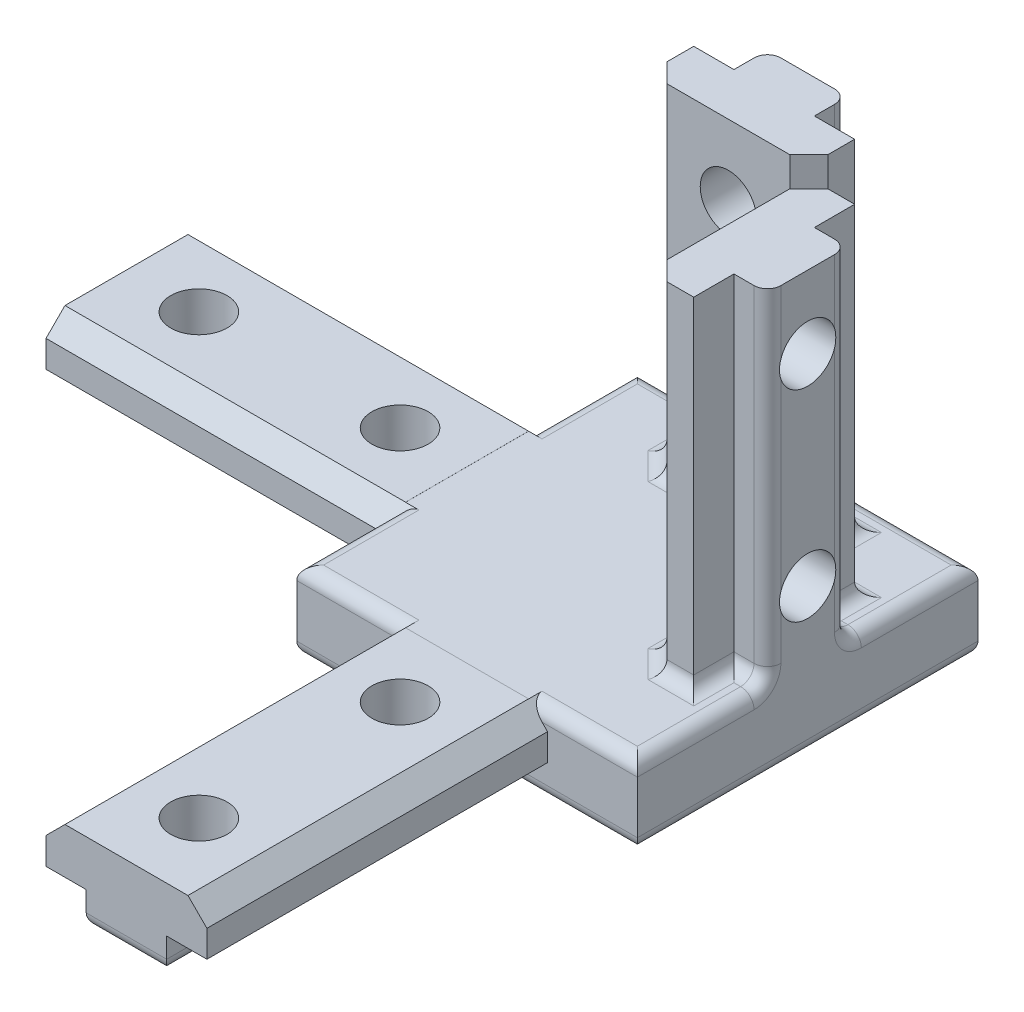
SolidWorks part; units mm, degrees
ref_plane "Front Plane" through (0, 0, 0) normal (0, 0, 1) x (1, 0, 0)
ref_plane "Top Plane" through (0, 0, 0) normal (0, 1, 0) x (1, 0, 0)
ref_plane "Right Plane" through (0, 0, 0) normal (1, 0, 0) x (0, 0, -1)
sketch "Sketch1" plane through (0, 0, 0) normal (0, 1, 0) x (1, 0, 0)
  line L1 (-12.7, 12.7) -> (12.7, 12.7)
  line L2 (-12.7, 12.7) -> (-12.7, -12.7)
  line L3 (-12.7, -12.7) -> (12.7, -12.7)
  line L4 (12.7, 12.7) -> (12.7, -12.7)
  line L5 (-12.7, 12.7) -> (12.7, -12.7) construction
  line L6 (-12.7, -12.7) -> (12.7, 12.7) construction
  point P0 (0, 0)
  dimension "D1" = 25.4
extrude "Boss-Extrude1" add sketch "Sketch1" along normal blind 5.91
sketch "Sketch2" plane through (0, 0, 12.7) normal (0, 0, 1) x (1, 0, 0)
  line L0 (-3, 0) -> (3, 0)
  line L1 (-12.7, 0) -> (12.7, 0) construction
  line L2 (3, 0) -> (3, 2.5)
  line L3 (3, 2.5) -> (6, 2.5)
  line L4 (6, 2.5) -> (6, 4.5)
  line L5 (6, 4.5) -> (4.5858, 5.9142)
  line L6 (4.5858, 5.9142) -> (-4.5858, 5.9142)
  line L7 (0, 0) -> (0, 6.6193) construction
  line L8 (-6, 4.5) -> (-4.5858, 5.9142)
  line L9 (-6, 2.5) -> (-6, 4.5)
  line L10 (-3, 2.5) -> (-6, 2.5)
  line L11 (-3, 0) -> (-3, 2.5)
  point P14 (0, 5.9142)
  point P18 (0, 0)
  dimension "D1" = 6
  dimension "D2" = 12
  dimension "D3" = 135
  dimension "D4" = 2.5
  dimension "D5" = 2
extrude "Boss-Extrude2" add sketch "Sketch2" along normal blind 25.4
sketch "Sketch3" plane through (-12.7, 0, 0) normal (-1, 0, 0) x (0, 0, 1)
  line L0 (-3, 0) -> (3, 0)
  line L1 (3, 0) -> (3, 2.5)
  line L2 (3, 2.5) -> (6, 2.5)
  line L3 (6, 2.5) -> (6, 4.5)
  line L4 (6, 4.5) -> (4.5858, 5.9142)
  line L5 (4.5858, 5.9142) -> (-4.5858, 5.9142)
  line L6 (0, 0) -> (0, 6.6193) construction
  line L7 (-6, 4.5) -> (-4.5858, 5.9142)
  line L8 (-6, 2.5) -> (-6, 4.5)
  line L9 (-3, 2.5) -> (-6, 2.5)
  line L10 (-3, 0) -> (-3, 2.5)
  point P9 (0, 5.9142)
  point P13 (0, 0)
  dimension "D1" = 6
  dimension "D2" = 12
  dimension "D3" = 2.5
  dimension "D4" = 2
  dimension "D5" = 135
extrude "Boss-Extrude3" add sketch "Sketch3" along normal blind 25.4
sketch "Sketch5" plane through (0, 5.91, 0) normal (0, 1, 0) x (1, 0, 0)
  line L0 (3, 12.7) -> (-3, 12.7)
  line L1 (-3, 12.7) -> (-3, 10.2)
  line L2 (-3, 10.2) -> (-6, 10.2)
  line L3 (-6, 10.2) -> (-6, 8.2)
  line L4 (-6, 8.2) -> (-4.5858, 6.7858)
  line L5 (-4.5858, 6.7858) -> (4.5858, 6.7858)
  line L6 (0, 3.4686) -> (0, -3.1261) construction
  line L7 (6, 8.2) -> (4.5858, 6.7858)
  line L8 (6, 10.2) -> (6, 8.2)
  line L9 (3, 10.2) -> (6, 10.2)
  line L10 (3, 12.7) -> (3, 10.2)
  line L11 (12.7, 12.7) -> (-12.7, 12.7) construction
  line L12 (12.7, -3) -> (12.7, 3)
  line L13 (12.7, 3) -> (10.2, 3)
  line L14 (10.2, 3) -> (10.2, 6)
  line L15 (10.2, 6) -> (8.2, 6)
  line L16 (8.2, 6) -> (6.7858, 4.5858)
  line L17 (6.7858, 4.5858) -> (6.7858, -4.5858)
  line L18 (6.7858, 0) -> (12.7, 0) construction
  line L19 (8.2, -6) -> (6.7858, -4.5858)
  line L20 (10.2, -6) -> (8.2, -6)
  line L21 (10.2, -3) -> (10.2, -6)
  line L22 (12.7, -3) -> (10.2, -3)
  line L23 (12.7, -12.7) -> (12.7, 12.7) construction
  point P9 (0, 6.7858)
  point P13 (0, 12.7)
  point P27 (6.7858, 0)
  point P31 (12.7, 0)
  dimension "D1" = 6
  dimension "D2" = 12
  dimension "D3" = 2.5
  dimension "D4" = 2
  dimension "D5" = 135
  dimension "D6" = 2.5
  dimension "D7" = 6
  dimension "D8" = 12
  dimension "D9" = 2
  dimension "D10" = 135
  dimension "D11" = 135
extrude "Boss-Extrude4" add sketch "Sketch5" along normal blind 25.4
fillet "Fillet2" radius 1 42 edges at (3, 18.61, -12.7) (12.7, 18.61, -3) (12.7, 18.61, 3) (-3, 18.61, -12.7) (-6, 5.91, -9.2) (-5.2929, 5.91, -7.4929) (0, 5.91, -6.7858) (5.2929, 5.91, -7.4929) (6, 5.91, -9.2) (4.5, 5.91, -10.2) (3, 5.91, -11.45) (7.85, 5.91, -12.7) (12.7, 5.91, -7.85) (11.45, 5.91, -3) (10.2, 5.91, -4.5) (9.2, 5.91, -6) (7.4929, 5.91, -5.2929) (6.7858, 5.91, 0) (7.4929, 5.91, 5.2929) (9.2, 5.91, 6) (10.2, 5.91, 4.5) (11.45, 5.91, 3) (12.7, 5.91, 7.85) (8.645, 5.91, 12.7) (-8.645, 5.91, 12.7) (-12.7, 5.91, 8.645) (-12.7, 5.91, -8.645) (-7.85, 5.91, -12.7) (-3, 5.91, -11.45) (-4.5, 5.91, -10.2) (0, 0, -12.7) (-12.7, 0, -7.85) (-25.4, 0, -3) (-38.1, 0, 0) (-25.4, 0, 3) (-12.7, 0, 7.85) (-7.85, 0, 12.7) (-3, 0, 25.4) (0, 0, 38.1) (3, 0, 25.4) (7.85, 0, 12.7) (12.7, 0, 0)
hole_wizard "M5x0.8 Tapped Hole2" positions "Sketch8" profile "Sketch9" tap size "M5x0.8" standard "ANSI Metric" end condition through all
sketch "Sketch8" plane through (0, 0, 0) normal (0, -1, 0) x (-1, 0, 0)
  line L0 (12.7, 6) -> (12.7, 3) construction
  line L1 (6, -12.7) -> (3, -12.7) construction
  point P0 (0, -17.7)
  point P2 (0, -32.7)
  point P4 (17.7, 0)
  point P6 (32.7, 0)
  dimension "D1" = 5
  dimension "D2" = 15
  dimension "D3" = 5
  dimension "D4" = 15
sketch "Sketch9" plane through (0, 0, 17.7) normal (1, 0, 0) x (0, 0, -1)
  line L0 (0, 0) -> (0, 31.31)
  line L1 (0, 31.31) -> (2.1, 31.31)
  line L2 (2.1, 31.31) -> (2.1, 0)
  line L5 (2.1, 0) -> (0, 0)
  line L11 (0, -6.35) -> (0, 107.95) construction
  dimension "Thru Tap Drill Dia." = 4.2
  dimension "Thru Tap Drill Depth" = 31.31
cosmetic thread "Hole Thread3" parameters "D2"=5
cosmetic thread "Hole Thread4" parameters "D2"=5
cosmetic thread "Hole Thread11" parameters "D2"=5
cosmetic thread "Hole Thread12" parameters "D2"=5
hole_wizard "M5x0.8 Tapped Hole3" positions "Sketch10" profile "Sketch11" tap size "M5x0.8" standard "ANSI Metric" end condition through all
sketch "Sketch10" plane through (12.7, 0, 0) normal (1, 0, 0) x (0, 0, -1)
  line L0 (-4, 5.91) -> (-7, 5.91) construction
  point P0 (0, 10.91)
  point P2 (0, 25.91)
  dimension "D1" = 5
  dimension "D2" = 15
sketch "Sketch11" plane through (12.7, 10.91, 0) normal (0, 1, 0) x (0, 0, -1)
  line L0 (0, 0) -> (0, 50.8)
  line L1 (0, 50.8) -> (2.1, 50.8)
  line L2 (2.1, 50.8) -> (2.1, 0)
  line L5 (2.1, 0) -> (0, 0)
  line L11 (0, -6.35) -> (0, 107.95) construction
  dimension "Thru Tap Drill Dia." = 4.2
  dimension "Thru Tap Drill Depth" = 50.8
cosmetic thread "Hole Thread13" parameters "D2"=5
cosmetic thread "Hole Thread14" parameters "D2"=5
hole_wizard "M5x0.8 Tapped Hole4" positions "Sketch12" profile "Sketch13" tap size "M5x0.8" standard "ANSI Metric" end condition through all
sketch "Sketch12" plane through (0, 0, -12.7) normal (0, 0, -1) x (-1, 0, 0)
  line L0 (-4, 5.91) -> (-7, 5.91) construction
  point P0 (0, 25.91)
  point P2 (0, 10.91)
  dimension "D1" = 5
  dimension "D2" = 15
sketch "Sketch13" plane through (0, 25.91, -12.7) normal (1, 0, 0) x (0, 1, 0)
  line L0 (0, 0) -> (0, 50.8)
  line L1 (0, 50.8) -> (2.1, 50.8)
  line L2 (2.1, 50.8) -> (2.1, 0)
  line L5 (2.1, 0) -> (0, 0)
  line L11 (0, -6.35) -> (0, 107.95) construction
  dimension "Thru Tap Drill Dia." = 4.2
  dimension "Thru Tap Drill Depth" = 50.8
cosmetic thread "Hole Thread10" parameters "D2"=5
cosmetic thread "Hole Thread15" parameters "D2"=5
equation "\"Insert Lengths\"= 1in"
equation "\"D1@Boss-Extrude2\"=\"Insert Lengths\""
equation "\"D1@Boss-Extrude4\"=\"Insert Lengths\""
